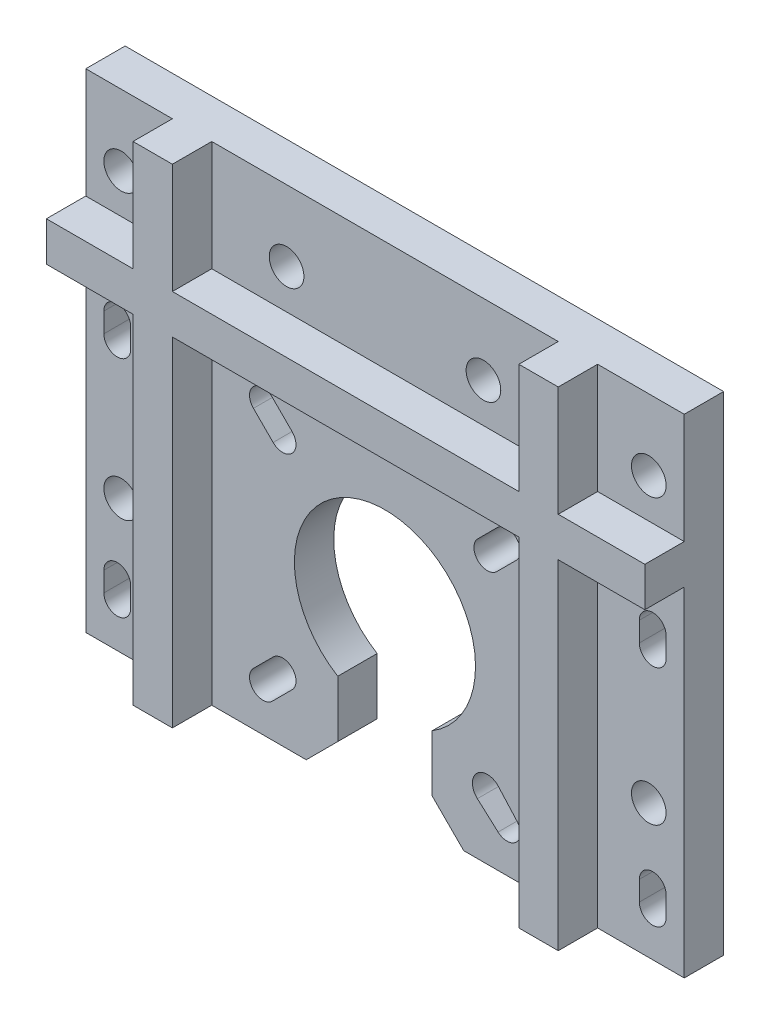
SolidWorks part; units mm, degrees
ref_plane "Front Plane" through (0, 0, 0) normal (0, 0, 1) x (1, 0, 0)
ref_plane "Top Plane" through (0, 0, 0) normal (0, 1, 0) x (1, 0, 0)
ref_plane "Right Plane" through (0, 0, 0) normal (1, 0, 0) x (0, 0, -1)
ref_plane "Plane1" through (0, 0, 0) normal (0, 0, -1) x (-1, 0, 0)
sketch "Sketch1" plane through (0, 0, 0) normal (0, 0, -1) x (-1, 0, 0)
  line L0 (-38, 62) -> (-38, 0)
  line L1 (-38, 0) -> (38, 0)
  line L2 (38, 0) -> (38, 62)
  line L3 (38, 62) -> (-38, 62)
extrude "Boss-Extrude1" add sketch "Sketch1" against normal blind 10
sketch "Sketch2" plane through (0, 0, 0) normal (0, -1, 0) x (1, 0, 0)
  line L0 (-22, 10) -> (-22, 5)
  line L1 (-22, 5) -> (22, 5)
  line L2 (22, 5) -> (22, 10)
  line L3 (22, 10) -> (-22, 10)
extrude "Cut-Extrude1" cut sketch "Sketch2" against normal blind 43
sketch "Sketch3" plane through (0, 0, 5) normal (0, 0, 1) x (1, 0, 0)
  line L0 (-6, 0) -> (6, 0)
  line L1 (6, 0) -> (6, 11.1928)
  line L2 (-6, 11.1858) -> (-6, 0)
  arc A0 (6, 11.1928) -> (-6, 11.1858) centre (-0.0057, 21) cw
extrude "Cut-Extrude2" cut sketch "Sketch3" against normal through all
sketch "Sketch4" plane through (0, 0, 5) normal (0, 0, 1) x (1, 0, 0)
  line L0 (-11.8037, 35.2021) -> (-14.3037, 37.7021)
  line L1 (-16.7078, 35.2979) -> (-14.2078, 32.7979)
  arc A0 (-14.2078, 32.7979) -> (-11.8037, 35.2021) centre (-13.0057, 34) ccw
  arc A1 (-14.3037, 37.7021) -> (-16.7078, 35.2979) centre (-15.5057, 36.5) ccw
extrude "Cut-Extrude3" cut sketch "Sketch4" against normal through all
sketch "Sketch5" plane through (0, 0, 5) normal (0, 0, 1) x (1, 0, 0)
  line L0 (-14.2078, 9.2021) -> (-16.7078, 6.7021)
  line L1 (-14.3037, 4.2979) -> (-11.8037, 6.7979)
  arc A0 (-16.7078, 6.7021) -> (-14.3037, 4.2979) centre (-15.5057, 5.5) ccw
  arc A1 (-11.8037, 6.7979) -> (-14.2078, 9.2021) centre (-13.0057, 8) ccw
extrude "Cut-Extrude4" cut sketch "Sketch5" against normal through all
sketch "Sketch6" plane through (0, 0, 5) normal (0, 0, 1) x (1, 0, 0)
  line L0 (11.7305, 6.5894) -> (14.3599, 4.2338)
  line L1 (16.7604, 6.6344) -> (14.4048, 9.2637)
  arc A0 (14.3599, 4.2338) -> (16.7604, 6.6344) centre (15.4943, 5.5) ccw
  arc A1 (14.4048, 9.2637) -> (11.7305, 6.5894) centre (12.9943, 8) ccw
extrude "Cut-Extrude5" cut sketch "Sketch6" against normal through all
sketch "Sketch7" plane through (0, 0, 0) normal (0, 0, -1) x (-1, 0, 0)
  line L0 (-16.6963, 35.2979) -> (-14.1963, 32.7979)
  line L1 (-11.7922, 35.2021) -> (-14.2922, 37.7021)
  arc A0 (-14.1963, 32.7979) -> (-11.7922, 35.2021) centre (-12.9943, 34) ccw
  arc A1 (-14.2922, 37.7021) -> (-16.6963, 35.2979) centre (-15.4943, 36.5) ccw
extrude "Cut-Extrude6" cut sketch "Sketch7" against normal through all
sketch "Sketch8" plane through (0, 0, 0) normal (0, -1, 0) x (1, 0, 0)
  line L0 (27, 5) -> (38, 5)
  line L1 (38, 5) -> (38, 10)
  line L2 (38, 10) -> (27, 10)
  line L3 (27, 10) -> (27, 5)
extrude "Cut-Extrude7" cut sketch "Sketch8" against normal blind 43
sketch "Sketch9" plane through (0, 0, 0) normal (0, 0, -1) x (-1, 0, 0)
  line L0 (-32.3, 34) -> (-32.3, 36.5)
  line L1 (-35.7, 36.5) -> (-35.7, 34)
  arc A0 (-32.3, 36.5) -> (-35.7, 36.5) centre (-34, 36.5) ccw
  arc A1 (-35.7, 34) -> (-32.3, 34) centre (-34, 34) ccw
extrude "Cut-Extrude8" cut sketch "Sketch9" against normal through all
sketch "Sketch10" plane through (0, 0, 0) normal (0, -1, 0) x (1, 0, 0)
  line L0 (-38, 5) -> (-27, 5)
  line L1 (-27, 5) -> (-27, 10)
  line L2 (-27, 10) -> (-38, 10)
  line L3 (-38, 10) -> (-38, 5)
extrude "Cut-Extrude9" cut sketch "Sketch10" against normal blind 43
sketch "Sketch11" plane through (0, 0, 5) normal (0, 0, 1) x (1, 0, 0)
  line L0 (-35.7, 36.5) -> (-35.7, 34)
  line L1 (-32.3, 34) -> (-32.3, 36.5)
  arc A0 (-32.3, 36.5) -> (-35.7, 36.5) centre (-34, 36.5) ccw
  arc A1 (-35.7, 34) -> (-32.3, 34) centre (-34, 34) ccw
extrude "Cut-Extrude10" cut sketch "Sketch11" against normal through all
sketch "Sketch12" plane through (0, 0, 0) normal (0, 0, -1) x (-1, 0, 0)
  line L0 (32.3, 8) -> (32.3, 5.5)
  line L1 (35.7, 5.5) -> (35.7, 8)
  arc A0 (35.7, 8) -> (32.3, 8) centre (34, 8) ccw
  arc A1 (32.3, 5.5) -> (35.7, 5.5) centre (34, 5.5) ccw
extrude "Cut-Extrude11" cut sketch "Sketch12" against normal through all
sketch "Sketch13" plane through (0, 0, 5) normal (0, 0, 1) x (1, 0, 0)
  line L0 (35.7, 5.5) -> (35.7, 8)
  line L1 (32.3, 8) -> (32.3, 5.5)
  arc A0 (35.7, 8) -> (32.3, 8) centre (34, 8) ccw
  arc A1 (32.3, 5.5) -> (35.7, 5.5) centre (34, 5.5) ccw
extrude "Cut-Extrude12" cut sketch "Sketch13" against normal through all
sketch "Sketch14" plane through (0, 62, 0) normal (0, 1, 0) x (-1, 0, 0)
  line L0 (-38, 10) -> (-38, 5)
  line L1 (-38, 5) -> (-27, 5)
  line L2 (-27, 5) -> (-27, 10)
  line L3 (-27, 10) -> (-38, 10)
extrude "Cut-Extrude13" cut sketch "Sketch14" against normal blind 14
sketch "Sketch15" plane through (0, 62, 0) normal (0, 1, 0) x (-1, 0, 0)
  line L0 (27, 10) -> (27, 5)
  line L1 (27, 5) -> (38, 5)
  line L2 (38, 5) -> (38, 10)
  line L3 (38, 10) -> (27, 10)
extrude "Cut-Extrude14" cut sketch "Sketch15" against normal blind 14
sketch "Sketch16" plane through (0, 62, 0) normal (0, 1, 0) x (-1, 0, 0)
  line L0 (-22, 10) -> (-22, 5)
  line L1 (-22, 5) -> (22, 5)
  line L2 (22, 5) -> (22, 10)
  line L3 (22, 10) -> (-22, 10)
extrude "Cut-Extrude15" cut sketch "Sketch16" against normal blind 14
ref_plane "Plane2" through (0, 21, 0) normal (0, 1, 0) x (-1, 0, 0)
sketch "Sketch17" plane through (0, 21, 0) normal (0, 1, 0) x (-1, 0, 0)
  line L0 (-11.4943, 0) -> (0.0057, 0)
  line L1 (0.0057, 0) -> (0.0057, 5)
  line L2 (0.0057, 5) -> (-11.4943, 5)
  line L3 (-11.4943, 5) -> (-11.4943, 0)
  line L4 (0.0057, 0) -> (0.0057, 5) construction
revolve "Cut-Revolve1" cut sketch "Sketch17" angle 360 about L4
hole_wizard "Hole1" positions "Sketch19" profile "Sketch18" legacy
sketch "Sketch19" plane through (0, 0, 5) normal (0, 0, 1) x (1, 0, 0)
  point P0 (-33.5, 17)
sketch "Sketch18" plane through (-33.5, 17, 5) normal (1, 0, 0) x (0, -1, 0)
  line L0 (0, 0) -> (0, 5)
  line L1 (0, 5) -> (2.2, 5)
  line L2 (2.2, 5) -> (2.2, 0)
  line L3 (2.2, 0) -> (0, 0)
  line L4 (0, 110) -> (0, -10) construction
  dimension "Diameter" = 4.4
  dimension "Depth" = 5
hole_wizard "Hole2" positions "Sketch21" profile "Sketch20" legacy
sketch "Sketch21" plane through (0, 0, 5) normal (0, 0, 1) x (1, 0, 0)
  point P0 (33.5, 17)
sketch "Sketch20" plane through (33.5, 17, 5) normal (1, 0, 0) x (0, -1, 0)
  line L0 (0, 0) -> (0, 5)
  line L1 (0, 5) -> (2.2, 5)
  line L2 (2.2, 5) -> (2.2, 0)
  line L3 (2.2, 0) -> (0, 0)
  line L4 (0, 110) -> (0, -10) construction
  dimension "Diameter" = 4.4
  dimension "Depth" = 5
hole_wizard "Hole3" positions "Sketch23" profile "Sketch22" legacy
sketch "Sketch23" plane through (0, 0, 5) normal (0, 0, 1) x (1, 0, 0)
  point P0 (33.5, 53)
sketch "Sketch22" plane through (33.5, 53, 5) normal (1, 0, 0) x (0, -1, 0)
  line L0 (0, 0) -> (0, 5)
  line L1 (0, 5) -> (2.2, 5)
  line L2 (2.2, 5) -> (2.2, 0)
  line L3 (2.2, 0) -> (0, 0)
  line L4 (0, 110) -> (0, -10) construction
  dimension "Diameter" = 4.4
  dimension "Depth" = 5
hole_wizard "Hole4" positions "Sketch25" profile "Sketch24" legacy
sketch "Sketch25" plane through (0, 0, 5) normal (0, 0, 1) x (1, 0, 0)
  point P0 (-33.5, 53)
sketch "Sketch24" plane through (-33.5, 53, 5) normal (1, 0, 0) x (0, -1, 0)
  line L0 (0, 0) -> (0, 5)
  line L1 (0, 5) -> (2.2, 5)
  line L2 (2.2, 5) -> (2.2, 0)
  line L3 (2.2, 0) -> (0, 0)
  line L4 (0, 110) -> (0, -10) construction
  dimension "Diameter" = 4.4
  dimension "Depth" = 5
hole_wizard "Hole5" positions "Sketch27" profile "Sketch26" legacy
sketch "Sketch27" plane through (0, 0, 5) normal (0, 0, 1) x (1, 0, 0)
  point P0 (-12.5, 53)
sketch "Sketch26" plane through (-12.5, 53, 5) normal (1, 0, 0) x (0, -1, 0)
  line L0 (0, 0) -> (0, 5)
  line L1 (0, 5) -> (2.2, 5)
  line L2 (2.2, 5) -> (2.2, 0)
  line L3 (2.2, 0) -> (0, 0)
  line L4 (0, 110) -> (0, -10) construction
  dimension "Diameter" = 4.4
  dimension "Depth" = 5
hole_wizard "Hole6" positions "Sketch29" profile "Sketch28" legacy
sketch "Sketch29" plane through (0, 0, 5) normal (0, 0, 1) x (1, 0, 0)
  point P0 (12.5, 53)
sketch "Sketch28" plane through (12.5, 53, 5) normal (1, 0, 0) x (0, -1, 0)
  line L0 (0, 0) -> (0, 5)
  line L1 (0, 5) -> (2.2, 5)
  line L2 (2.2, 5) -> (2.2, 0)
  line L3 (2.2, 0) -> (0, 0)
  line L4 (0, 110) -> (0, -10) construction
  dimension "Diameter" = 4.4
  dimension "Depth" = 5
chamfer "Chamfer1" distance 4 angle 45 1 edges at (-6, 0, 2.5)
chamfer "Chamfer2" distance 4 angle 45 1 edges at (6, 0, 2.5)
